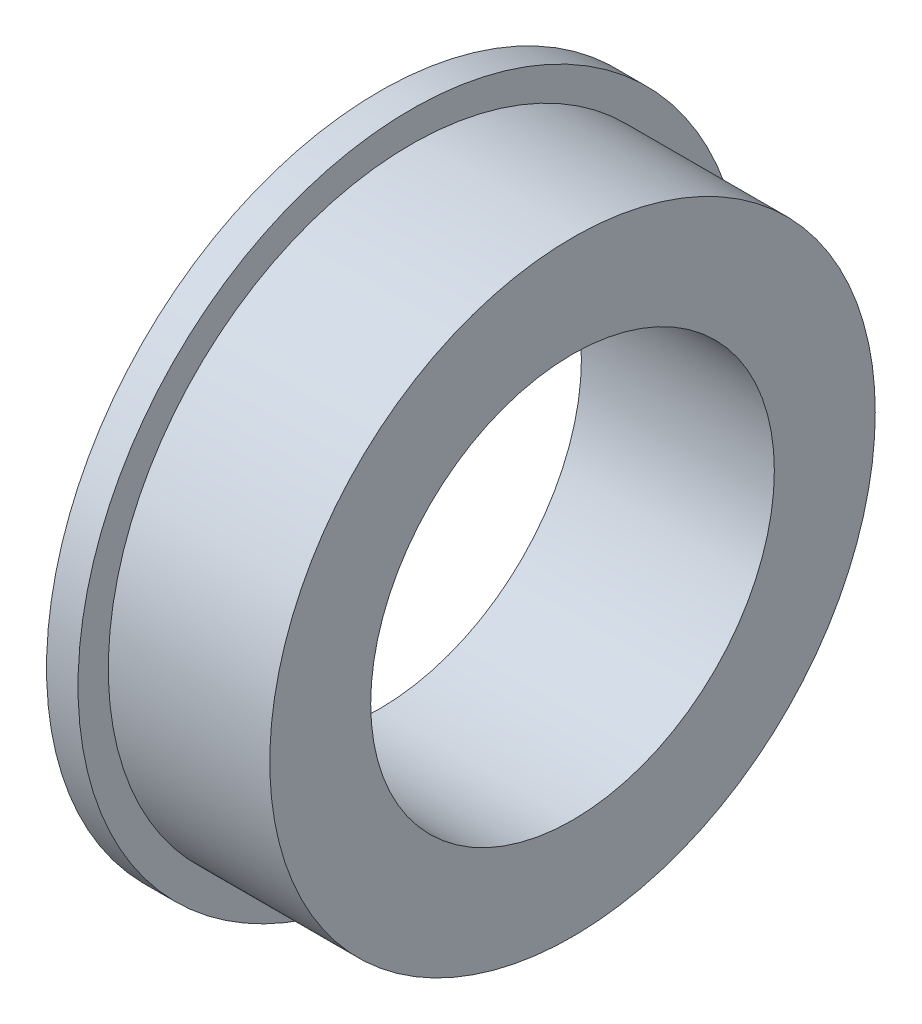
SolidWorks part; units mm, degrees
other "标注1"
sketch "草图4" plane through (4, 8.25, -8.25) normal (0.4479, 0.317, -0.836) x (-0.8659, -0.0791, -0.4939)
ref_plane "Front Plane" through (0, 0, 0) normal (0, 0, 1) x (1, 0, 0)
ref_plane "Top Plane" through (0, 0, 0) normal (0, 1, 0) x (1, 0, 0)
ref_plane "Right Plane" through (0, 0, 0) normal (1, 0, 0) x (0, 0, -1)
sketch "草图1" plane through (0, 0, 0) normal (1, 0, 0) x (0, 0, -1)
  circle A0 centre (0, 0) radius 5
  circle A1 centre (0, 0) radius 7.5
  dimension "D1" = 10
  dimension "D2" = 15
extrude "凸台-拉伸3" add sketch "草图1" along normal blind 4
sketch "草图3" plane through (0, 0, 0) normal (-1, 0, 0) x (0, 0, 1)
  circle A0 centre (0, 0) radius 8.25
  circle A1 centre (0, 0) radius 5
  dimension "D1" = 16.5
extrude "凸台-拉伸4" add sketch "草图3" along normal blind 0.78
